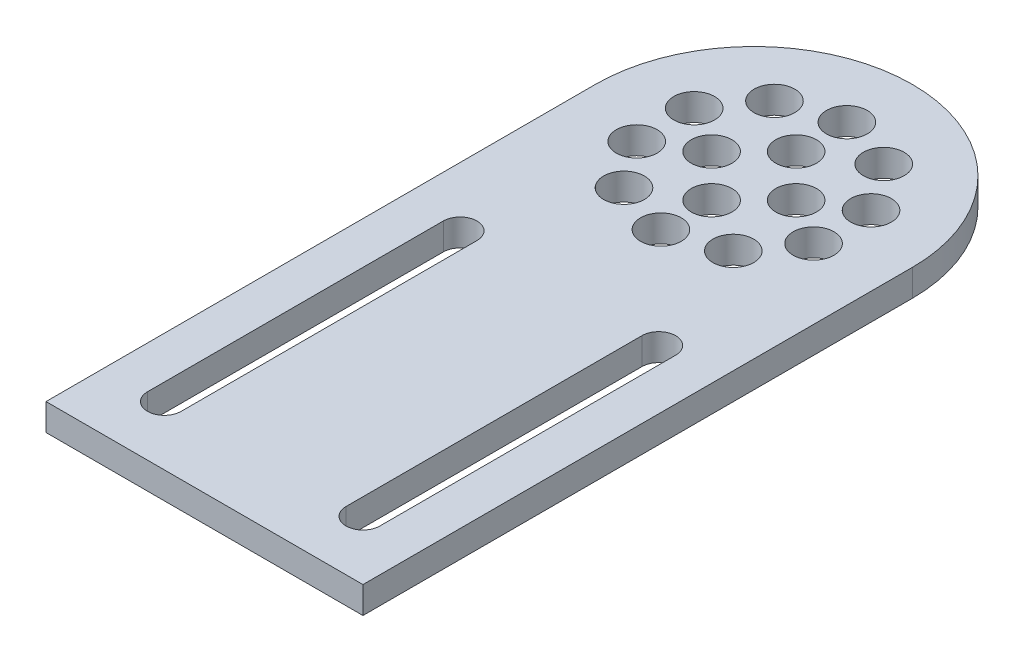
SolidWorks part; units mm, degrees
ref_plane "Front Plane" through (0, 0, 0) normal (0, 0, 1) x (1, 0, 0)
ref_plane "Top Plane" through (0, 0, 0) normal (0, 1, 0) x (1, 0, 0)
ref_plane "Right Plane" through (0, 0, 0) normal (1, 0, 0) x (0, 0, -1)
sketch "Sketch1" plane through (0, 0, 0) normal (0, 1, 0) x (1, 0, 0)
  line L0 (-37.5, 0) -> (-37.5, -130)
  line L1 (-37.5, -130) -> (37.5, -130)
  line L2 (37.5, -130) -> (37.5, 0)
  arc A0 (37.5, 0) -> (-37.5, 0) centre (0, 0) ccw
  circle A1 centre (0, 22) radius 4.825
  circle A2 centre (0, 10) radius 4.825
  circle A3 centre (12.9313, 17.7984) radius 4.825
  circle A4 centre (20.9232, 6.7984) radius 4.825
  circle A5 centre (20.9232, -6.7984) radius 4.825
  circle A6 centre (12.9313, -17.7984) radius 4.825
  circle A7 centre (0, -22) radius 4.825
  circle A8 centre (-12.9313, -17.7984) radius 4.825
  circle A9 centre (-20.9232, -6.7984) radius 4.825
  circle A10 centre (-20.9232, 6.7984) radius 4.825
  circle A11 centre (-12.9313, 17.7984) radius 4.825
  circle A12 centre (10, 0) radius 4.825
  circle A13 centre (0, -10) radius 4.825
  circle A14 centre (-10, 0) radius 4.825
  point P27 (0, 0)
  point P35 (0, 0)
  dimension "D1" = 9.65
  dimension "D2" = 75
  dimension "D5" = 10
  dimension "D6" = 12
  dimension "D7" = 130
  dimension "D3" = 10
  dimension "D4" = 4
extrude "Boss-Extrude1" add sketch "Sketch1" along normal blind 6.35
sketch "Sketch2" plane through (0, 6.35, 0) normal (0, 1, 0) x (1, 0, 0)
  line L0 (-23.5, -116) -> (-23.5, -46) construction
  line L1 (-27.5, -116) -> (-27.5, -46)
  line L2 (-19.5, -116) -> (-19.5, -46)
  line L3 (-37.5, -130) -> (37.5, -130) construction
  line L6 (-37.5, 0) -> (-37.5, -130) construction
  arc A0 (-27.5, -116) -> (-19.5, -116) centre (-23.5, -116) ccw
  arc A1 (-19.5, -46) -> (-27.5, -46) centre (-23.5, -46) ccw
  point P2 (-23.5, -81)
  point P14 (0, 0)
  point P15 (0, 0)
  dimension "D2" = 4
  dimension "D1" = 70
  dimension "D3" = 10
  dimension "D4" = 14
extrude "Cut-Extrude1" cut sketch "Sketch2" against normal through all
mirror "Mirror1" about plane through (0, 0, 0) normal (1, 0, 0) of "Cut-Extrude1"
